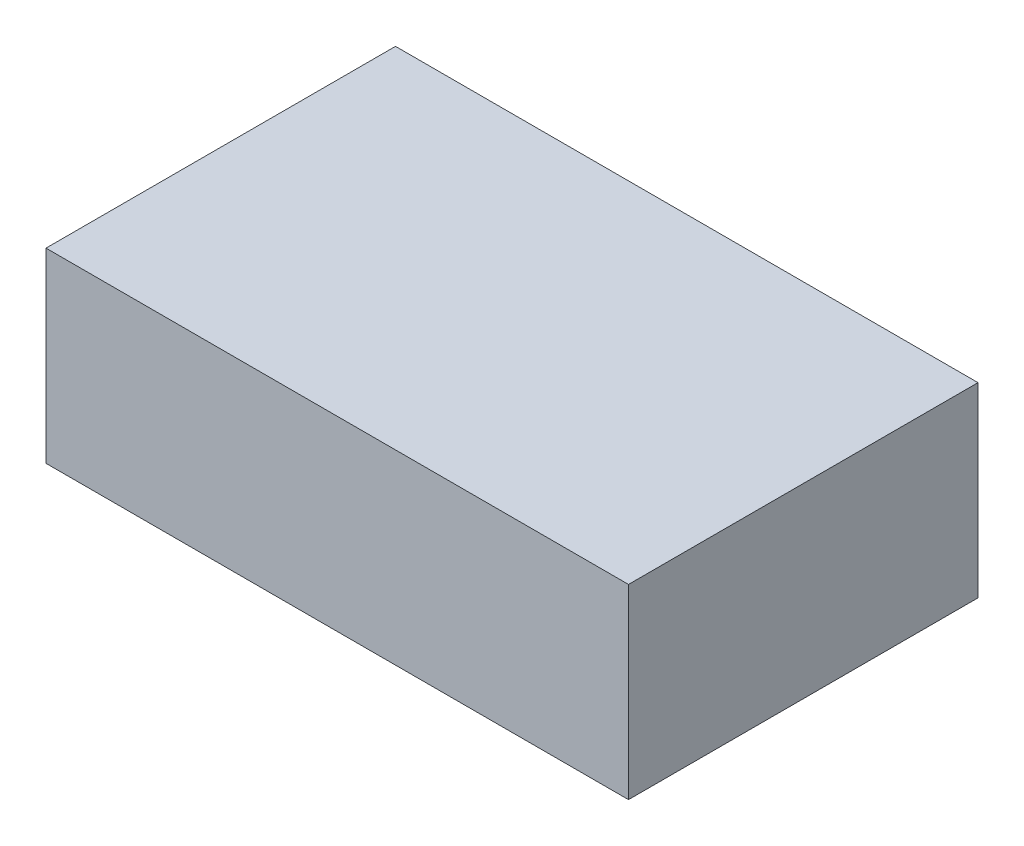
SolidWorks part; units mm, degrees
ref_plane "Ön Düzlem" through (0, 0, 0) normal (0, 0, 1) x (1, 0, 0)
ref_plane "Üst Düzlem" through (0, 0, 0) normal (0, 1, 0) x (1, 0, 0)
ref_plane "Sağ Düzlem" through (0, 0, 0) normal (1, 0, 0) x (0, 0, -1)
sketch "Sketch1" plane through (0, 0, 0) normal (0, 0, 1) x (1, 0, 0)
  line L1 (-9.5748, 2.1907) -> (15.4252, 2.1907)
  line L2 (-9.5748, 2.1907) -> (-9.5748, -5.8093)
  line L3 (-9.5748, -5.8093) -> (15.4252, -5.8093)
  line L4 (15.4252, 2.1907) -> (15.4252, -5.8093)
  dimension "D1" = 25
  dimension "D2" = 8
extrude "Boss-Extrude2" add sketch "Sketch1" along normal blind 15
